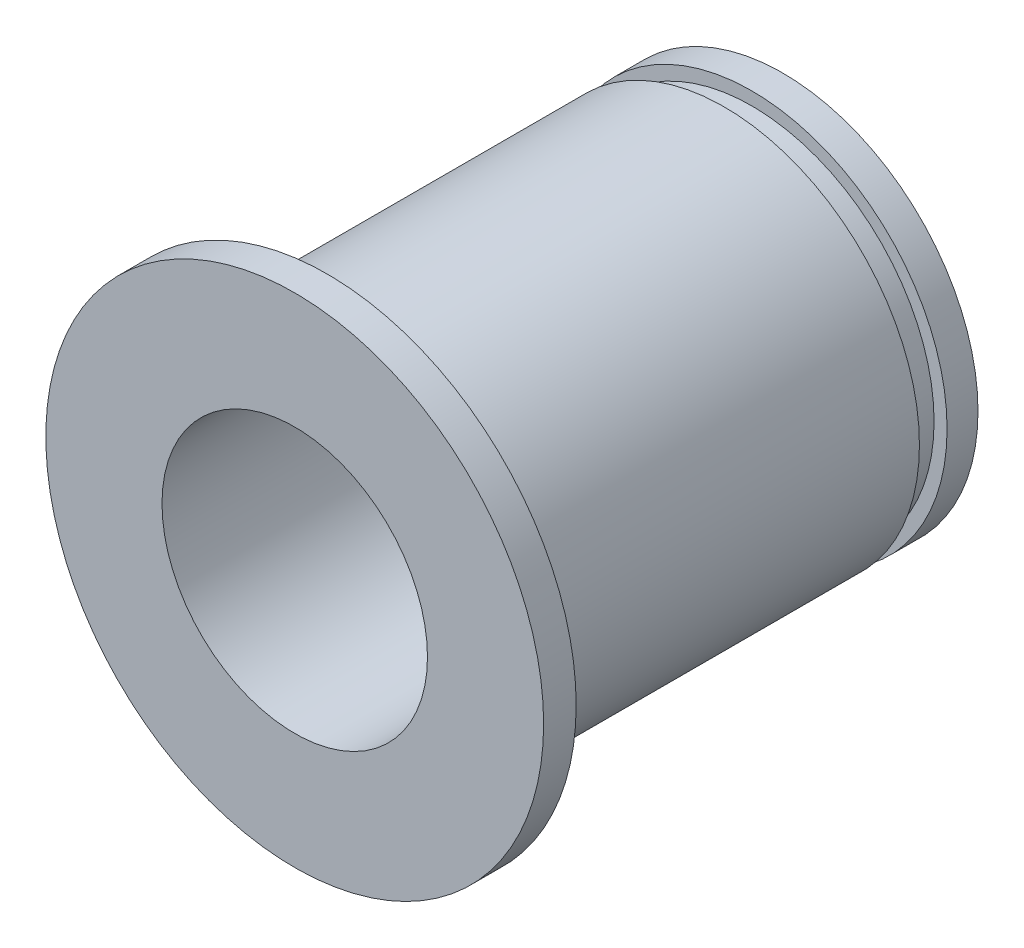
SolidWorks part; units mm, degrees
ref_plane "Front Plane" through (0, 0, 0) normal (0, 0, 1) x (1, 0, 0)
ref_plane "Top Plane" through (0, 0, 0) normal (0, 1, 0) x (1, 0, 0)
ref_plane "Right Plane" through (0, 0, 0) normal (1, 0, 0) x (0, 0, -1)
sketch "S01 - Ground guide bore and body" plane through (0, 0, 0) normal (0, 0, 1) x (1, 0, 0)
  circle A0 centre (0, 0) radius 6
  circle A1 centre (0, 0) radius 4.08
  dimension "D1" = 8.16
  dimension "D2" = 12
extrude "01 - Ground guide bore and body" add sketch "S01 - Ground guide bore and body" along normal blind 14 from offset 2
sketch "S02 - Outboard flange" plane through (0, 0, 0) normal (0, 0, 1) x (1, 0, 0)
  circle A0 centre (0, 0) radius 7.65
  circle A1 centre (0, 0) radius 4.08
  dimension "D1" = 8.16
  dimension "D2" = 15.3
extrude "02 - Outboard flange" add sketch "S02 - Outboard flange" along normal blind 1 from offset 12
sketch "S03 - External retaining ring groove" plane through (0, 0, 0) normal (0, 0, 1) x (1, 0, 0)
  circle A0 centre (0, 0) radius 6.1
  circle A1 centre (0, 0) radius 5.6
  dimension "D1" = 11.2
  dimension "D2" = 12.2
extrude "03 - External retaining ring groove" cut sketch "S03 - External retaining ring groove" along normal blind 0.85 from offset 1.05
